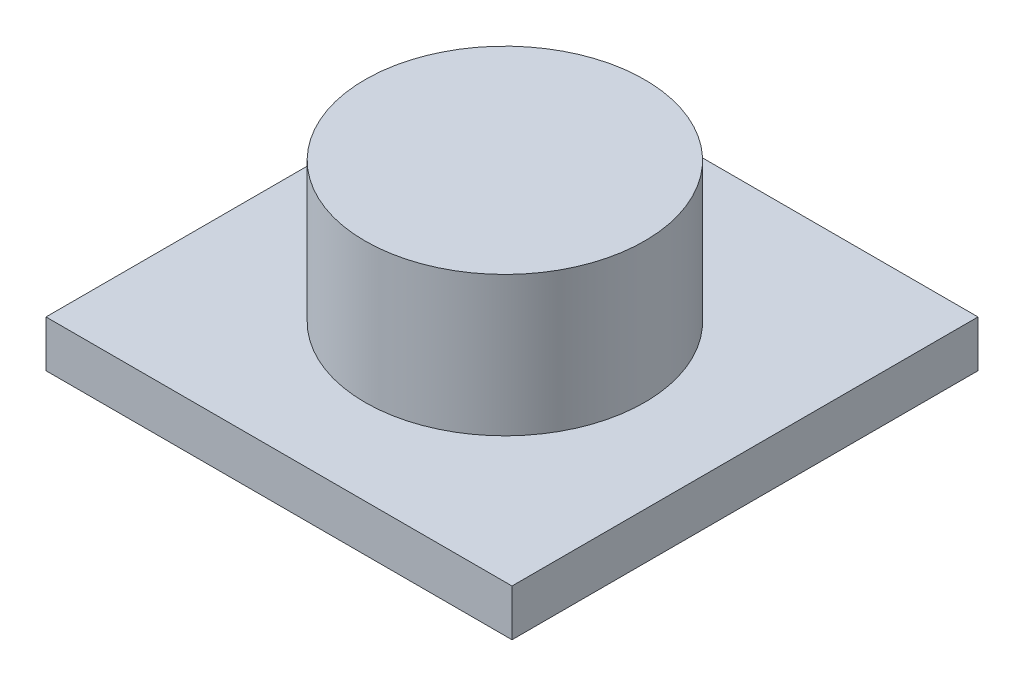
SolidWorks part; units mm, degrees
ref_plane "Front Plane" through (0, 0, 0) normal (0, 0, 1) x (1, 0, 0)
ref_plane "Top Plane" through (0, 0, 0) normal (0, 1, 0) x (1, 0, 0)
ref_plane "Right Plane" through (0, 0, 0) normal (1, 0, 0) x (0, 0, -1)
sketch "Sketch1" plane through (0, 0, 0) normal (0, 1, 0) x (1, 0, 0)
  line L1 (-5.0125, 4.0585) -> (4.9875, 4.0585)
  line L2 (-5.0125, 4.0585) -> (-5.0125, -5.9415)
  line L3 (-5.0125, -5.9415) -> (4.9875, -5.9415)
  line L4 (4.9875, 4.0585) -> (4.9875, -5.9415)
  dimension "D1" = 10
  dimension "D2" = 10
extrude "Boss-Extrude1" add sketch "Sketch1" along normal blind 1
sketch "Sketch2" plane through (0, 1, 0) normal (0, 1, 0) x (1, 0, 0)
  circle A0 centre (0, -1.107) radius 3
extrude "Boss-Extrude2" add sketch "Sketch2" along normal blind 3
